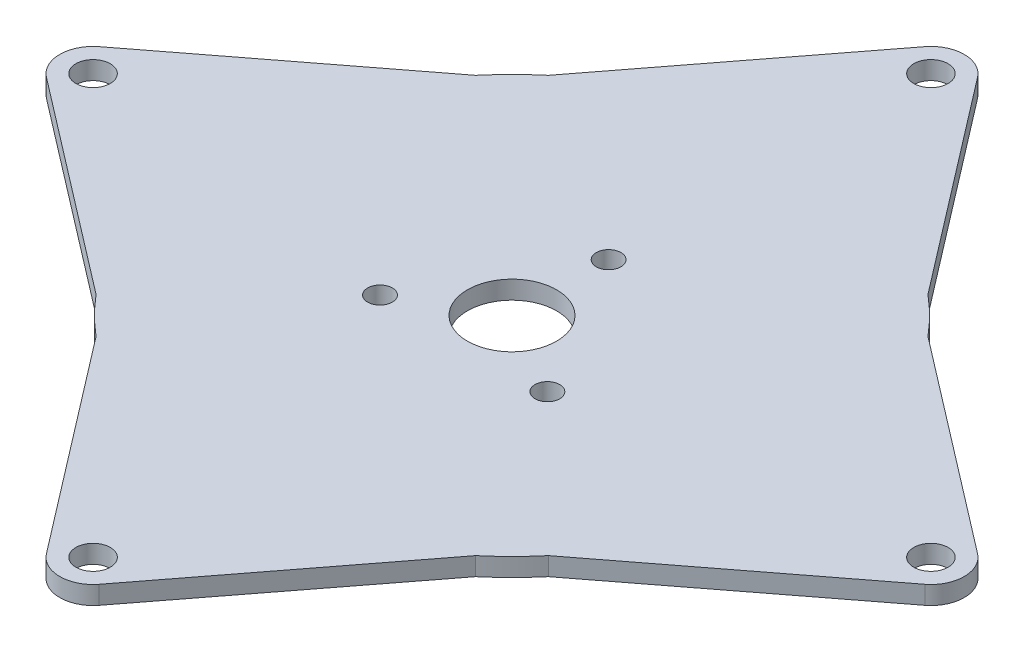
SolidWorks part; units mm, degrees
other "motor_mount" parameters "D1"=97.7653, "D2"=14.7748, "D5"=1.5153, "D6"=1.2729, "D7"=2.6145, "D8"=27.5115, "D9"=27.5368, "D10"=3, "D11"=7.957, "D12"=2, "D14"=6.8142, "D15"=5.6048, "D3"=9, "D4"=4.1559, "D13"=13.0555
material "6061-T6 (SS)"
ref_plane "Front Plane" through (0, 0, 0) normal (0, 0, 1) x (1, 0, 0)
ref_plane "Top Plane" through (0, 0, 0) normal (0, 1, 0) x (1, 0, 0)
ref_plane "Right Plane" through (0, 0, 0) normal (1, 0, 0) x (0, 0, -1)
sketch "Sketch1" plane through (0, 0, 0) normal (0, 1, 0) x (1, 0, 0)
  line L0 (0, 0) -> (0, 9) construction
  line L1 (0, 0) -> (7.7942, -4.5) construction
  line L2 (0, 0) -> (-7.7942, -4.5) construction
  line L3 (-2.4599, -40.9065) -> (-17.6737, -21.0687)
  line L4 (0, 0) -> (39.02, 0) construction
  line L5 (17.6737, -21.0687) -> (2.4599, -40.9065)
  line L6 (-40.9065, 2.4599) -> (-21.0687, 17.6737)
  line L7 (21.0687, 17.6737) -> (40.9065, 2.4599)
  line L8 (40.9065, -2.4599) -> (21.0687, -17.6737)
  line L9 (-21.0687, -17.6737) -> (-40.9065, -2.4599)
  line L10 (2.4599, 40.9065) -> (17.6737, 21.0687)
  line L11 (-17.6737, 21.0687) -> (-2.4599, 40.9065)
  line L12 (0, 0) -> (21.0687, 17.6737) construction
  circle A0 centre (0, 0) radius 27.5 construction
  circle A1 centre (0, 0) radius 9 construction
  circle A2 centre (0, 9) radius 1.15
  circle A3 centre (7.7942, -4.5) radius 1.15
  circle A4 centre (-7.7942, -4.5) radius 1.15
  circle A8 centre (39.02, 0) radius 1.6
  circle A9 centre (0, 0) radius 4.15
  arc A11 (40.9065, -2.4599) -> (40.9065, 2.4599) centre (39.02, 0) ccw
  circle A12 centre (0, 0) radius 27.5
  arc A14 (-2.4599, -40.9065) -> (2.4599, -40.9065) centre (0, -39.02) ccw
  circle A16 centre (0, -39.02) radius 1.6
  arc A18 (-40.9065, 2.4599) -> (-40.9065, -2.4599) centre (-39.02, 0) ccw
  circle A19 centre (-39.02, 0) radius 1.6
  arc A20 (2.4599, 40.9065) -> (-2.4599, 40.9065) centre (0, 39.02) ccw
  circle A21 centre (0, 39.02) radius 1.6
  dimension "D1" = 55
  dimension "D2" = 18
  dimension "D7" = 2.3
  dimension "D11" = 8.3
  dimension "D12" = 3.2
  dimension "D3" = 120
  dimension "D4" = 120
  dimension "D13" = 39.02
  dimension "D15" = 1.5
  dimension "D5" = 25
  dimension "D8" = 27.5
  dimension "D9" = 21.0687
  dimension "D6" = 4
extrude "Boss-Extrude2" add sketch "Sketch1" along normal blind 1.7
equation "\"Hwidth\"= 39.02"
equation "\"D13@Sketch1\"=\"Hwidth\""
equation "\"Mdia\"=2.3"
equation "\"D7@Sketch1\"=\"Mdia\""
equation "\"Shaft\"=8.3"
equation "\"D11@Sketch1\"=\"Shaft\""
equation "\"Mounthole\"=3.2"
equation "\"D12@Sketch1\"=\"Mounthole\""
equation "\"MainDia\"=55"
equation "\"D1@Sketch1\"=\"MainDia\""
